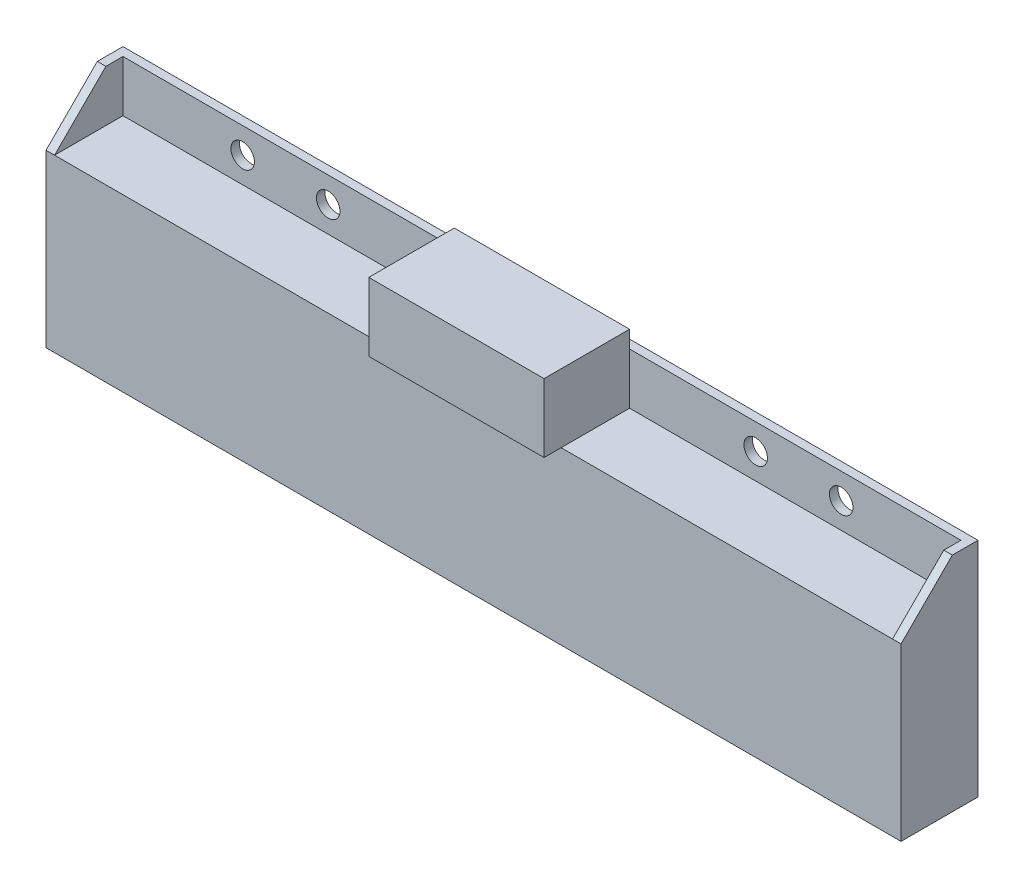
SolidWorks part; units mm, degrees
ref_plane "前视基准面" through (0, 0, 0) normal (0, 0, 1) x (1, 0, 0)
ref_plane "上视基准面" through (0, 0, 0) normal (0, 1, 0) x (1, 0, 0)
ref_plane "右视基准面" through (0, 0, 0) normal (1, 0, 0) x (0, 0, -1)
sketch "草图1" plane through (0, 0, 0) normal (0, 0, 1) x (1, 0, 0)
  line L1 (100, -26) -> (-100, -26)
  line L2 (100, -26) -> (100, 26)
  line L3 (100, 26) -> (-100, 26)
  line L4 (-100, -26) -> (-100, 26)
  line L5 (100, -26) -> (-100, 26) construction
  line L6 (100, 26) -> (-100, -26) construction
  point P0 (0, 0)
  dimension "D1" = 200
  dimension "D2" = 52
extrude "凸台-拉伸1" add sketch "草图1" along normal blind 18
sketch "草图2" plane through (-100, 0, 0) normal (-1, 0, 0) x (0, 0, 1)
  line L0 (18, 14) -> (6, 26)
  line L1 (18, 26) -> (18, -26) construction
  line L2 (6, 26) -> (18, 26)
  line L3 (18, 26) -> (18, 14)
  line L4 (18, 26) -> (0, 26) construction
  line L5 (18, -26) -> (0, -26) construction
  line L6 (0, 26) -> (0, -26) construction
  dimension "D1" = 40
  dimension "D2" = 6
extrude "切除-拉伸1" cut sketch "草图2" against normal through all
sketch "草图3" plane through (0, 0, 18) normal (0, 0, 1) x (1, 0, 0)
  line L0 (100, 14) -> (-100, 14) construction
  line L1 (-98, 14) -> (98, 14)
  line L2 (-98, 14) -> (-98, 26)
  line L3 (-98, 26) -> (98, 26)
  line L4 (98, 14) -> (98, 26)
  line L5 (100, 26) -> (-100, 26) construction
  line L6 (-100, 26) -> (-100, 14) construction
  line L7 (100, 26) -> (100, 14) construction
  dimension "D1" = 2
  dimension "D2" = 2
extrude "切除-拉伸2" cut sketch "草图3" against normal offset from surface (16 mm away) 2 up to face at (0, 0, 0)
hole_wizard "M5 间隙孔1" positions "草图4" profile "草图5" hole size "M5" standard "GB" end condition up to next
sketch "草图4" plane through (0, 0, 2) normal (0, 0, 1) x (1, 0, 0)
  line L0 (0, 14) -> (0, 26) construction
  line L1 (-98, 26) -> (98, 26) construction
  line L3 (-98, 14) -> (98, 14) construction
  point P0 (-50, 20)
  point P2 (50, 20)
  point P4 (70, 20)
  point P6 (-70, 20)
  point P20 (0, 20)
  dimension "D1" = 100
  dimension "D2" = 140
sketch "草图5" plane through (-50, 20, 2) normal (1, 0, 0) x (0, -1, 0)
  line L0 (0, 0) -> (0, 2)
  line L1 (0, 2) -> (2.75, 2)
  line L2 (2.75, 2) -> (2.75, 0)
  line L5 (2.75, 0) -> (0, 0)
  line L11 (0, -6.35) -> (0, 107.95) construction
  dimension "通孔孔直径" = 5.5
  dimension "通孔孔深度" = 2
sketch "草图6" plane through (0, 0, 2) normal (0, 0, 1) x (1, 0, 0)
  line L0 (-98, 14) -> (98, 14) construction
  line L1 (-20.5, 30) -> (20.5, 30)
  line L2 (-20.5, 30) -> (-20.5, 14)
  line L3 (-20.5, 14) -> (20.5, 14)
  line L4 (20.5, 30) -> (20.5, 14)
  line L5 (0, 0) -> (0, 26) construction
  line L6 (-98, 26) -> (98, 26) construction
  dimension "D1" = 41
  dimension "D2" = 4
extrude "凸台-拉伸2" add sketch "草图6" along normal blind 20
ref_plane "基准面1" through (0, -46, 0) normal (0, -1, 0) x (-1, 0, 0)
ref_plane "基准面2" through (0, -66, 0) normal (0, -1, 0) x (-1, 0, 0)
